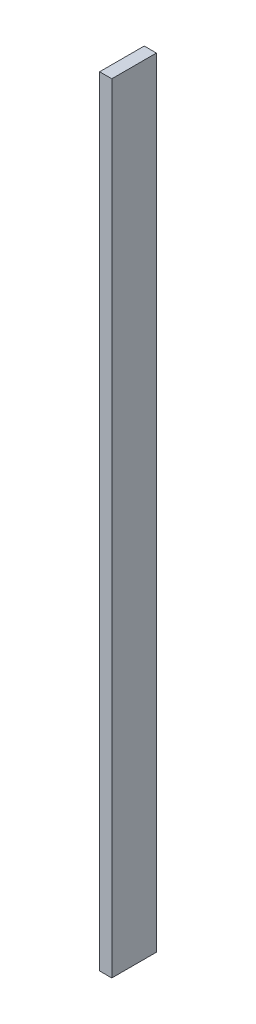
SolidWorks part; units mm, degrees
ref_plane "Front Plane" through (0, 0, 0) normal (0, 0, 1) x (1, 0, 0)
ref_plane "Top Plane" through (0, 0, 0) normal (0, 1, 0) x (1, 0, 0)
ref_plane "Right Plane" through (0, 0, 0) normal (1, 0, 0) x (0, 0, -1)
sketch "Sketch1" plane through (0, 0, 0) normal (0, 1, 0) x (1, 0, 0)
  line L1 (-19.05, -69.85) -> (19.05, -69.85)
  line L2 (-19.05, -69.85) -> (-19.05, 69.85)
  line L3 (-19.05, 69.85) -> (19.05, 69.85)
  line L4 (19.05, -69.85) -> (19.05, 69.85)
  line L5 (-19.05, -69.85) -> (19.05, 69.85) construction
  line L6 (-19.05, 69.85) -> (19.05, -69.85) construction
  point P0 (0, 0)
  dimension "D1" = 38.1
  dimension "D2" = 139.7
extrude "Boss-Extrude1" add sketch "Sketch1" along normal blind 2438.4
